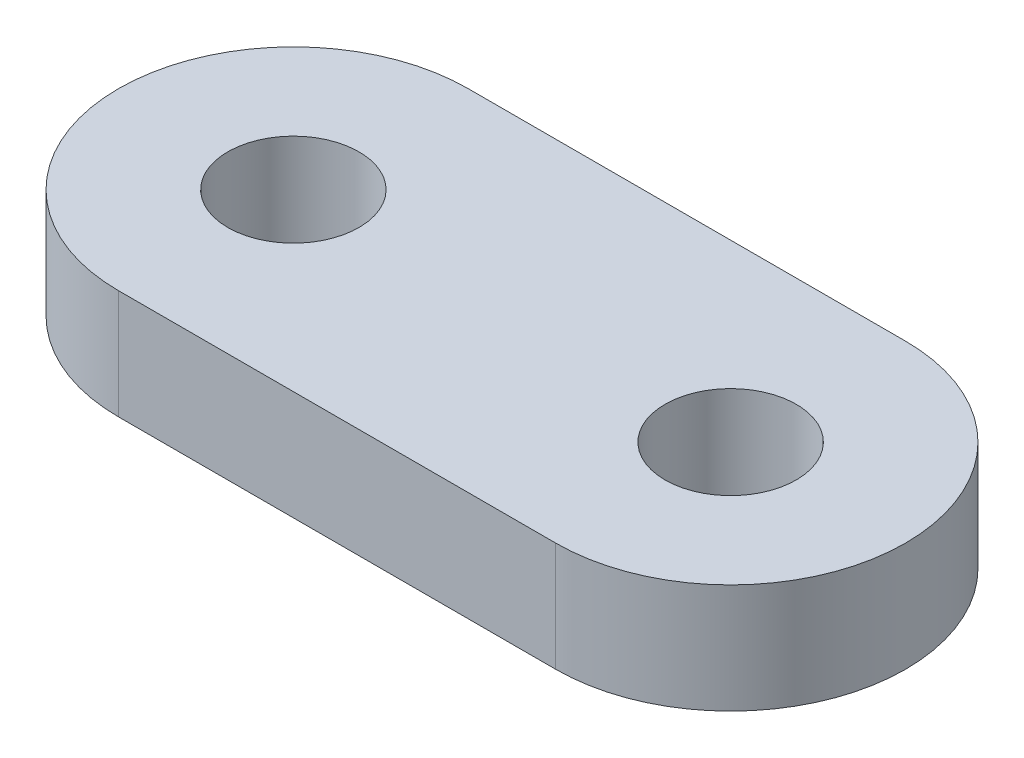
SolidWorks part; units mm, degrees
ref_plane "前基準面" through (0, 0, 0) normal (0, 0, 1) x (1, 0, 0)
ref_plane "上基準面" through (0, 0, 0) normal (0, 1, 0) x (1, 0, 0)
ref_plane "右基準面" through (0, 0, 0) normal (1, 0, 0) x (0, 0, -1)
sketch "草圖1" plane through (0, 0, 0) normal (0, 1, 0) x (1, 0, 0)
  line L0 (-35.9568, 0) -> (39.8148, 0) construction
  line L1 (-10, 0) -> (10, 0) construction
  line L2 (-10, 8) -> (10, 8)
  line L3 (-10, -8) -> (10, -8)
  arc A0 (-10, 8) -> (-10, -8) centre (-10, 0) ccw
  arc A1 (10, -8) -> (10, 8) centre (10, 0) ccw
  circle A2 centre (-10, 0) radius 3
  circle A3 centre (10, 0) radius 3
  point P5 (0, 0)
  dimension "D2" = 8
  dimension "D3" = 6
  dimension "D1" = 20
extrude "填料-伸長1" add sketch "草圖1" along normal blind 5
